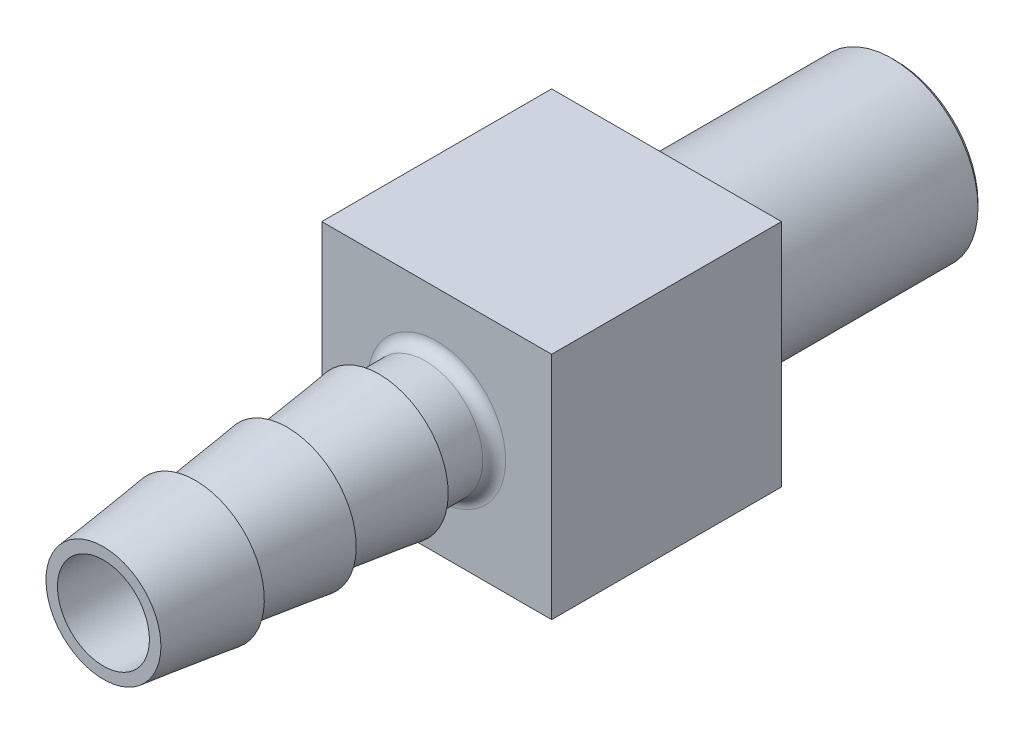
SolidWorks part; units mm, degrees
material "Brass"
ref_plane "Front Plane" through (0, 0, 0) normal (0, 0, 1) x (1, 0, 0)
ref_plane "Top Plane" through (0, 0, 0) normal (0, 1, 0) x (1, 0, 0)
ref_plane "Right Plane" through (0, 0, 0) normal (1, 0, 0) x (0, 0, -1)
sketch "Sketch1" plane through (0, 0, 0) normal (0, 0, 1) x (1, 0, 0)
  circle A0 centre (0, 0) radius 4.7625
  dimension "D1" = 9.525
extrude "Boss-Extrude1" add sketch "Sketch1" along normal blind 12.7
chamfer "Chamfer1" distance 0.254 angle 45 1 edges at (4.7625, 0, 0)
sketch "Sketch2" plane through (0, 0, 12.7) normal (0, 0, 1) x (1, 0, 0)
  line L1 (-6.35, 6.35) -> (6.35, 6.35)
  line L2 (-6.35, 6.35) -> (-6.35, -6.35)
  line L3 (-6.35, -6.35) -> (6.35, -6.35)
  line L4 (6.35, 6.35) -> (6.35, -6.35)
  dimension "D1" = 12.7
  dimension "D2" = 12.7
  dimension "D3" = 6.35
  dimension "D4" = 6.35
extrude "Boss-Extrude2" add sketch "Sketch2" along normal blind 12.7
sketch "Sketch3" plane through (0, 0, 0) normal (1, 0, 0) x (0, 0, -1)
  line L2 (-25.4, 3.175) -> (-28.575, 3.175)
  line L3 (-19.05, 0) -> (-94.6079, 0) construction
  line L4 (-25.4, -6.35) -> (-25.4, 6.35) construction
  line L5 (-28.575, 3.175) -> (-28.575, 3.81)
  line L6 (-28.575, 3.81) -> (-33.655, 3.175)
  line L7 (-33.655, 3.175) -> (-33.655, 3.81)
  line L8 (-33.655, 3.81) -> (-38.735, 3.175)
  line L9 (-38.735, 3.175) -> (-38.735, 3.81)
  line L10 (-38.735, 3.81) -> (-43.815, 3.175)
  line L11 (-43.815, 3.175) -> (-43.815, 0)
  line L12 (-43.815, 0) -> (-25.4, 0)
  line L15 (-25.4, 0) -> (-25.4, 3.175)
  dimension "D1" = 3.175
  dimension "D2" = 0.635
  dimension "D3" = 5.08
  dimension "D4" = 3.175
revolve "Revolve1" add sketch "Sketch3" angle 360 about L3
fillet "Fillet1" radius 0.635 2 edges at (4.7625, 0, 12.7) (3.175, 0, 25.4)
sketch "Sketch5" plane through (0, 0, 0) normal (0, 0, -1) x (-1, 0, 0)
  circle A0 centre (0, 0) radius 3.175
  dimension "D1" = 6.35
extrude "Cut-Extrude2" cut sketch "Sketch5" against normal blind 20.32
sketch "Sketch6" plane through (0, 0, 43.815) normal (0, 0, 1) x (1, 0, 0)
  circle A0 centre (0, 0) radius 2.54
  dimension "D1" = 5.08
extrude "Cut-Extrude3" cut sketch "Sketch6" against normal blind 23.876
